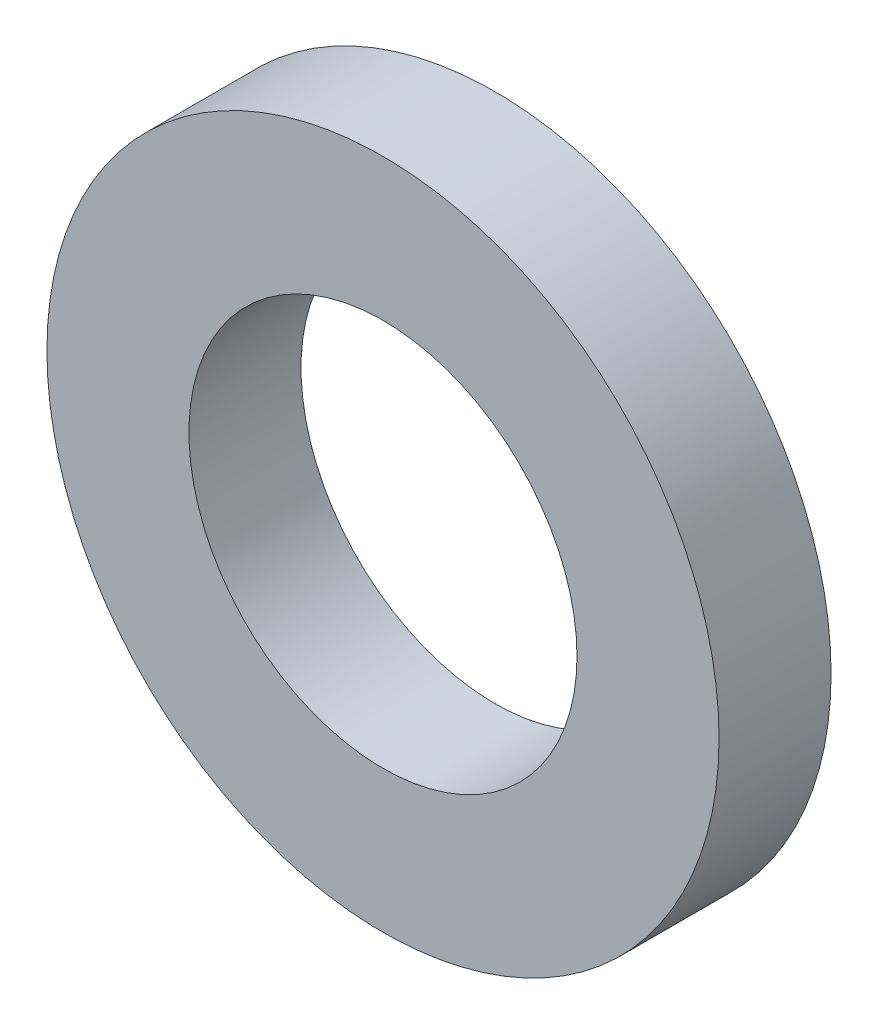
SolidWorks part; units mm, degrees
ref_plane "Front Plane" through (0, 0, 0) normal (0, 0, 1) x (1, 0, 0)
ref_plane "Top Plane" through (0, 0, 0) normal (0, 1, 0) x (1, 0, 0)
ref_plane "Right Plane" through (0, 0, 0) normal (1, 0, 0) x (0, 0, -1)
sketch "Sketch2" plane through (0, 0, 0) normal (0, 0, 1) x (1, 0, 0)
  circle A0 centre (0, 0) radius 10.9982
  dimension "D1" = 21.9964
sketch "Sketch4" plane through (0, 0, 0) normal (0, 0, 1) x (1, 0, 0)
  circle A0 centre (0, 0) radius 19.05
  dimension "D1" = 38.1
extrude "Boss-Extrude1" add sketch "Sketch4" along normal mid plane 6.35
extrude "Cut-Extrude1" cut sketch "Sketch2" against normal mid plane 25.4 contours A0
